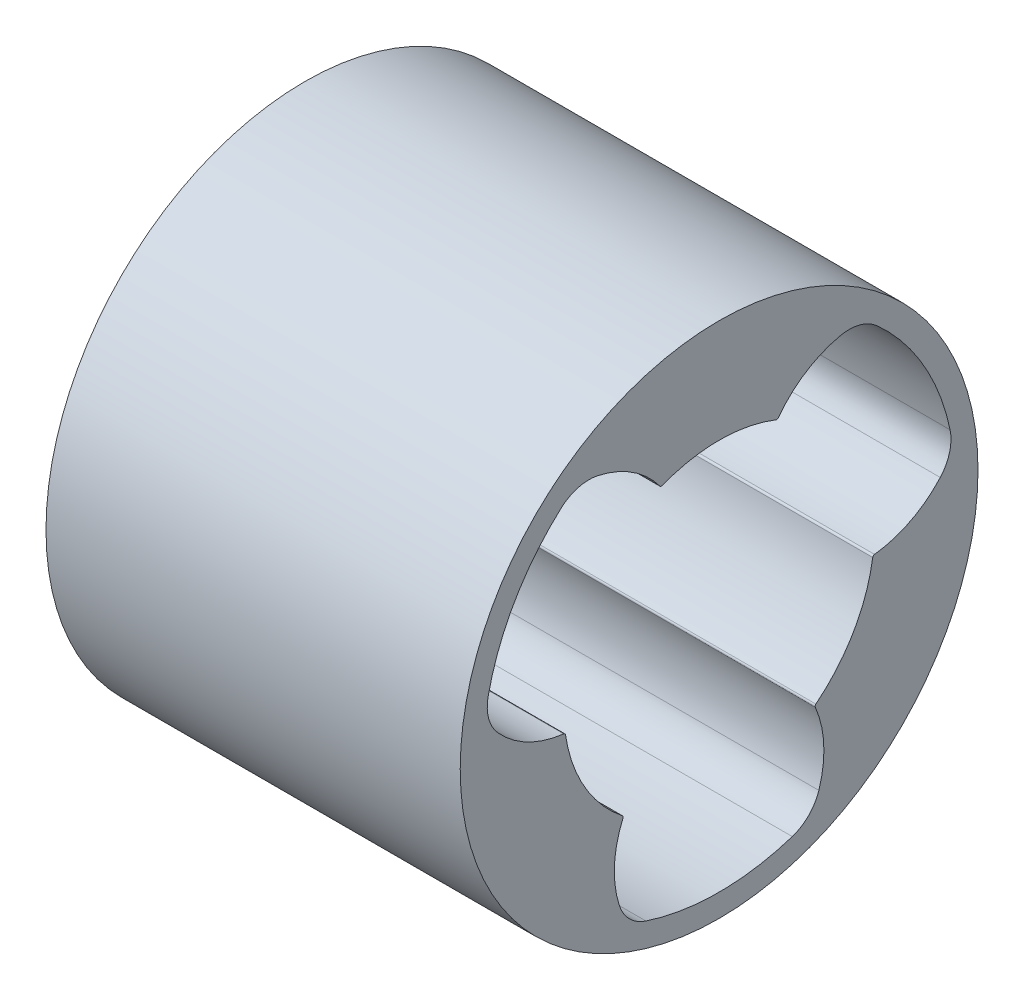
SolidWorks part; units mm, degrees
ref_plane "Front Plane" through (0, 0, 0) normal (0, 0, 1) x (1, 0, 0)
ref_plane "Top Plane" through (0, 0, 0) normal (0, 1, 0) x (1, 0, 0)
ref_plane "Right Plane" through (0, 0, 0) normal (1, 0, 0) x (0, 0, -1)
ref_plane "Plane1" through (0, 0, 0) normal (0, 0, -1) x (-1, 0, 0)
sketch "Sketch1" plane through (0, 0, 0) normal (0, 0, -1) x (-1, 0, 0)
  line L0 (-50.8, 31.75) -> (-50.8, 0)
  line L1 (-50.8, 0) -> (0, 0)
  line L2 (0, 0) -> (0, 31.75)
  line L3 (0, 31.75) -> (-50.8, 31.75)
  line L4 (-50.8, 0) -> (0, 0) construction
revolve "Revolve1" add sketch "Sketch1" angle 360 about L4
sketch "Sketch2" plane through (50.8, 0, 0) normal (1, 0, 0) x (0, 0, -1)
  arc A0 (-17.575, 23.0124) -> (-28.7168, 3.7142) centre (0, 0) ccw
  arc A1 (-28.7168, 3.7142) -> (-17.575, 23.0124) centre (-17.5976, 10.16) ccw
extrude "Cut-Extrude1" cut sketch "Sketch2" against normal blind 43.18
sketch "Sketch3" plane through (50.8, 0, 0) normal (1, 0, 0) x (0, 0, -1)
  arc A0 (-11.1418, -26.7266) -> (11.1418, -26.7266) centre (0, 0) ccw
  arc A1 (11.1418, -26.7266) -> (-11.1418, -26.7266) centre (0, -20.32) ccw
extrude "Cut-Extrude2" cut sketch "Sketch3" against normal blind 43.18
sketch "Sketch4" plane through (50.8, 0, 0) normal (1, 0, 0) x (0, 0, -1)
  arc A0 (28.7168, 3.7142) -> (17.575, 23.0124) centre (0, 0) ccw
  arc A1 (17.575, 23.0124) -> (28.7168, 3.7142) centre (17.5976, 10.16) ccw
extrude "Cut-Extrude3" cut sketch "Sketch4" against normal blind 43.18
hole_wizard "M36 Clearance Hole1" positions "Sketch6" profile "Sketch5" hole size "M36" standard "ANSI Metric"
sketch "Sketch6" plane through (0, 0, 0) normal (-1, 0, 0) x (0, 0, 1)
  point P0 (0, 0)
sketch "Sketch5" plane through (0, 0, 0) normal (0, 1, 0) x (0, 0, 1)
  line L0 (0, 0) -> (0, 50.8)
  line L1 (0, 50.8) -> (19.05, 50.8)
  line L2 (19.05, 50.8) -> (19.05, 0)
  line L5 (19.05, 0) -> (0, 0)
  line L11 (0, -6.35) -> (0, 107.95) construction
  dimension "Thru Hole Dia." = 38.1
  dimension "Thru Hole Depth" = 50.8
fillet "Fillet1" radius 5.08 6 edges at (29.21, 3.7142, 28.7168) (29.21, 23.0124, 17.575) (29.21, -26.7266, -11.1418) (29.21, -26.7266, 11.1418) (29.21, 23.0124, -17.575) (29.21, 3.7142, -28.7168)
fillet "Fillet2" radius 0.254 6 edges at (29.21, -2.6295, 18.8677) (29.21, 17.6546, 7.1566) (29.21, -2.6295, -18.8677) (29.21, 17.6546, -7.1566) (29.21, -15.0251, 11.711) (29.21, -15.0251, -11.711)
